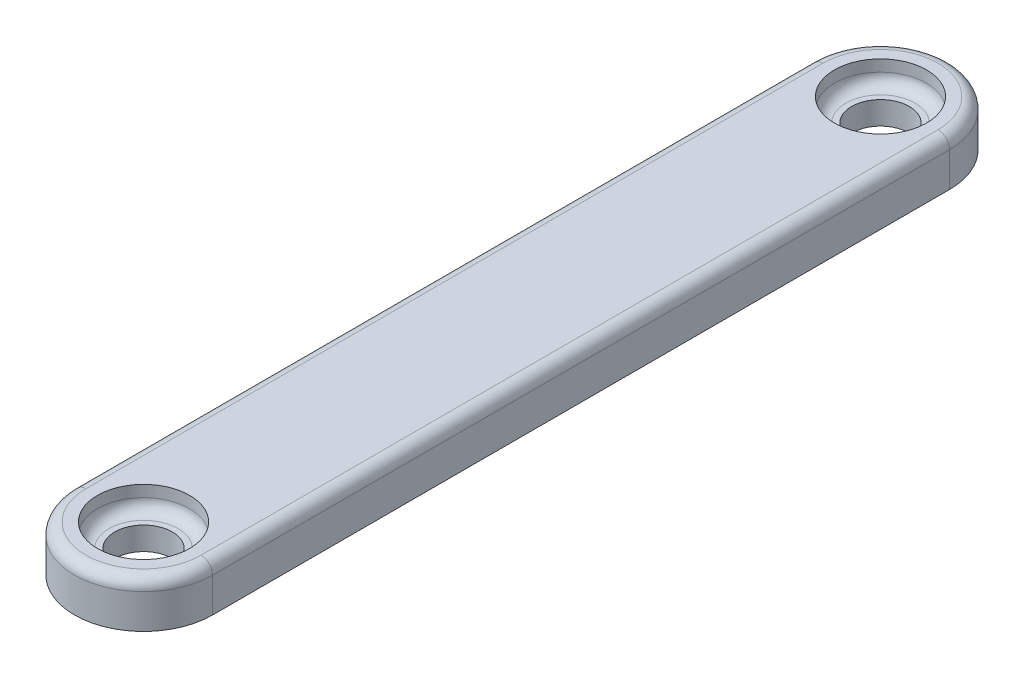
SolidWorks part; units mm, degrees
ref_plane "Front Plane" through (0, 0, 0) normal (0, 0, 1) x (1, 0, 0)
ref_plane "Top Plane" through (0, 0, 0) normal (0, 1, 0) x (1, 0, 0)
ref_plane "Right Plane" through (0, 0, 0) normal (1, 0, 0) x (0, 0, -1)
sketch "Sketch1" plane through (0, 0, 0) normal (0, 1, 0) x (1, 0, 0)
  line L0 (-3, -16) -> (-3, 16)
  line L1 (3, 16) -> (3, -16)
  arc A0 (-3, 16) -> (3, 16) centre (0, 16) cw
  arc A1 (3, -16) -> (-3, -16) centre (0, -16) cw
  circle A2 centre (0, 16) radius 1.25
  circle A3 centre (0, -16) radius 1.25
  point P8 (-3, 0)
  dimension "D1" = 3
  dimension "D3" = 2.5
  dimension "D2" = 32
extrude "Boss-Extrude1" add sketch "Sketch1" along normal blind 2
sketch "Sketch2" plane through (0, 2, 0) normal (0, 1, 0) x (1, 0, 0)
  line L0 (-1.1, 0) -> (1.1, 0) construction
  circle A0 centre (0, -16) radius 2
  circle A1 centre (0, 16) radius 2
  dimension "D1" = 4
extrude "Cut-Extrude1" cut sketch "Sketch2" against normal blind 1
fillet "Fillet1" radius 0.5 6 edges at (0, 2, 19) (-3, 2, 0) (0, 2, -19) (3, 2, 0) (0, 1, 18) (0, 1, -18)
